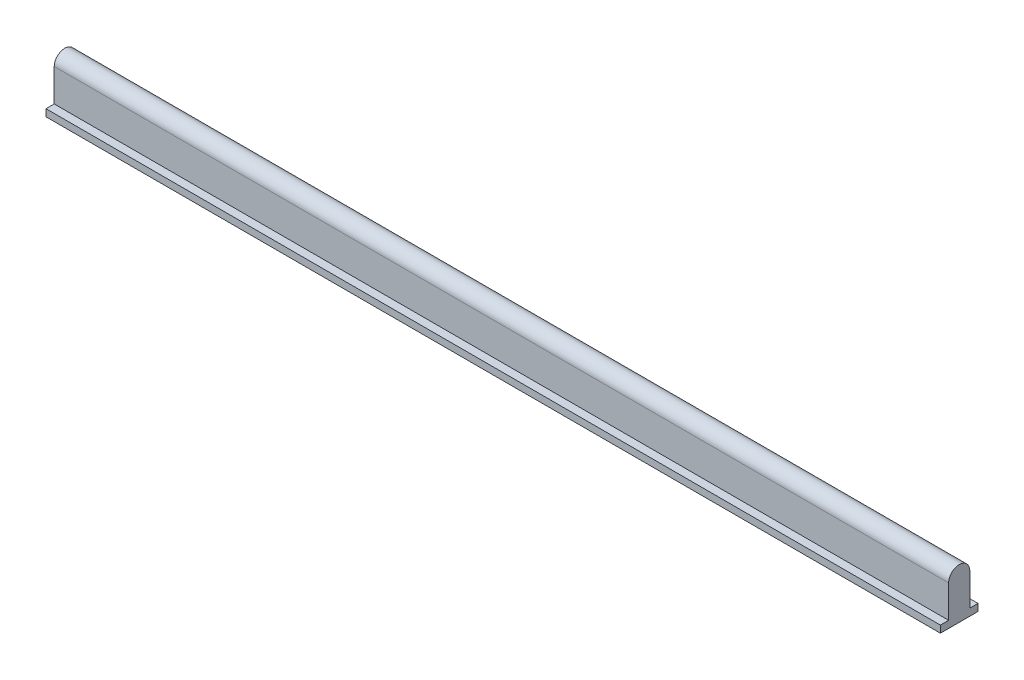
SolidWorks part; units mm, degrees
ref_plane "Front Plane" through (0, 0, 0) normal (0, 0, 1) x (1, 0, 0)
ref_plane "Top Plane" through (0, 0, 0) normal (0, 1, 0) x (1, 0, 0)
ref_plane "Right Plane" through (0, 0, 0) normal (1, 0, 0) x (0, 0, -1)
sketch "Sketch2" plane through (0, 0, 0) normal (1, 0, 0) x (0, 0, -1)
  line L0 (6, -20.0364) -> (10.6697, -20.0364)
  line L2 (-6, -1.6364) -> (-6, -20.0364)
  line L4 (6, -1.6364) -> (6, -20.0364)
  line L6 (-10.6697, -20.0364) -> (-10.6697, -24.0364)
  line L7 (-10.6697, -24.0364) -> (10.6697, -24.0364)
  line L8 (10.6697, -20.0364) -> (10.6697, -24.0364)
  line L9 (-6, -20.0364) -> (-10.6697, -20.0364)
  arc A0 (6, -1.6364) -> (-6, -1.6364) centre (0, -1.6364) ccw
  point P6 (0, -20.0364)
  dimension "D1" = 12
  dimension "D2" = 18.4
extrude "Boss-Extrude1" add sketch "Sketch2" along normal blind 507.8
